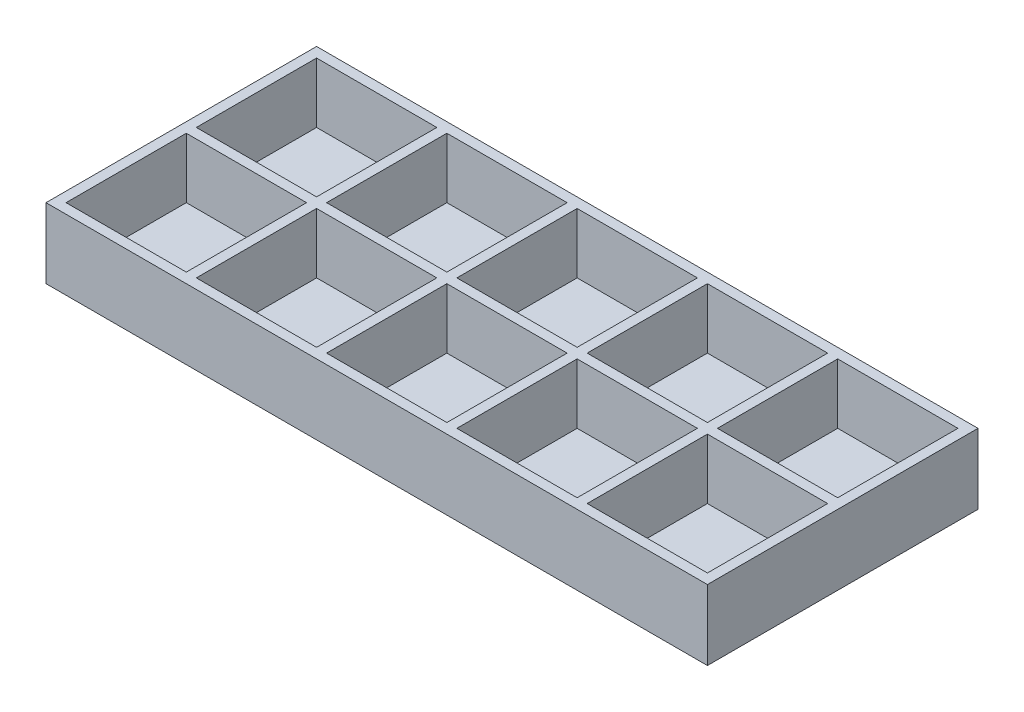
SolidWorks part; units mm, degrees
ref_plane "Alzado" through (0, 0, 0) normal (0, 0, 1) x (1, 0, 0)
ref_plane "Planta" through (0, 0, 0) normal (0, 1, 0) x (1, 0, 0)
ref_plane "Vista lateral" through (0, 0, 0) normal (1, 0, 0) x (0, 0, -1)
sketch "Croquis1" plane through (0, 0, 0) normal (0, 1, 0) x (1, 0, 0)
  line L1 (-165, -67.5) -> (165, -67.5)
  line L2 (-165, -67.5) -> (-165, 67.5)
  line L3 (-165, 67.5) -> (165, 67.5)
  line L4 (165, -67.5) -> (165, 67.5)
  line L5 (-165, -67.5) -> (165, 67.5) construction
  line L6 (-165, 67.5) -> (165, -67.5) construction
  point P0 (0, 0)
  dimension "D1" = 330
  dimension "D2" = 135
extrude "Saliente-Extruir1" add sketch "Croquis1" along normal blind 5
sketch "Croquis2" plane through (0, 5, 0) normal (0, 1, 0) x (1, 0, 0)
  line L0 (165, 67.5) -> (-165, 67.5) construction
  line L1 (-165, 67.5) -> (-165, -67.5) construction
  line L2 (-165, -67.5) -> (165, -67.5) construction
  line L3 (165, -67.5) -> (165, 67.5) construction
  line L4 (165, 67.5) -> (-165, 67.5)
  line L5 (-165, 67.5) -> (-165, -67.5)
  line L6 (-165, -67.5) -> (165, -67.5)
  line L7 (165, -67.5) -> (165, 67.5)
  line L9 (-160, 62.5) -> (-100, 62.5)
  line L10 (-160, 62.5) -> (-160, 2.5)
  line L11 (-160, 2.5) -> (-100, 2.5)
  line L12 (-100, 62.5) -> (-100, 2.5)
  line L13 (-95, 62.5) -> (-35, 62.5)
  line L14 (-95, 62.5) -> (-95, 2.5)
  line L15 (-95, 2.5) -> (-35, 2.5)
  line L16 (-35, 62.5) -> (-35, 2.5)
  line L17 (-30, 62.5) -> (30, 62.5)
  line L18 (-30, 62.5) -> (-30, 2.5)
  line L19 (-30, 2.5) -> (30, 2.5)
  line L20 (30, 62.5) -> (30, 2.5)
  line L21 (35, 62.5) -> (95, 62.5)
  line L22 (35, 62.5) -> (35, 2.5)
  line L23 (35, 2.5) -> (95, 2.5)
  line L24 (95, 62.5) -> (95, 2.5)
  line L25 (100, 62.5) -> (160, 62.5)
  line L26 (100, 62.5) -> (100, 2.5)
  line L27 (100, 2.5) -> (160, 2.5)
  line L28 (160, 62.5) -> (160, 2.5)
  line L29 (-160, -2.5) -> (-100, -2.5)
  line L30 (-160, -2.5) -> (-160, -62.5)
  line L31 (-160, -62.5) -> (-100, -62.5)
  line L32 (-100, -2.5) -> (-100, -62.5)
  line L33 (-95, -2.5) -> (-35, -2.5)
  line L34 (-95, -2.5) -> (-95, -62.5)
  line L35 (-95, -62.5) -> (-35, -62.5)
  line L36 (-35, -2.5) -> (-35, -62.5)
  line L37 (-30, -2.5) -> (30, -2.5)
  line L38 (-30, -2.5) -> (-30, -62.5)
  line L39 (-30, -62.5) -> (30, -62.5)
  line L40 (30, -2.5) -> (30, -62.5)
  line L41 (35, -2.5) -> (95, -2.5)
  line L42 (35, -2.5) -> (35, -62.5)
  line L43 (35, -62.5) -> (95, -62.5)
  line L44 (95, -2.5) -> (95, -62.5)
  line L45 (100, -2.5) -> (160, -2.5)
  line L46 (100, -2.5) -> (100, -62.5)
  line L47 (100, -62.5) -> (160, -62.5)
  line L48 (160, -2.5) -> (160, -62.5)
  point P44 (0, 0)
  point P45 (0, 0)
  point P46 (0, 0)
  point P47 (0, 0)
  point P48 (0, 0)
  point P49 (0, 0)
  point P50 (0, 0)
  point P51 (0, 0)
  point P52 (0, 0)
  dimension "D1" = 60
  dimension "D2" = 5
  dimension "D3" = 5
  dimension "D4" = 5
  dimension "D5" = 5
  dimension "D6" = 5
  dimension "D7" = 5
  dimension "D8" = 5
extrude "Saliente-Extruir2" add sketch "Croquis2" along normal blind 30
